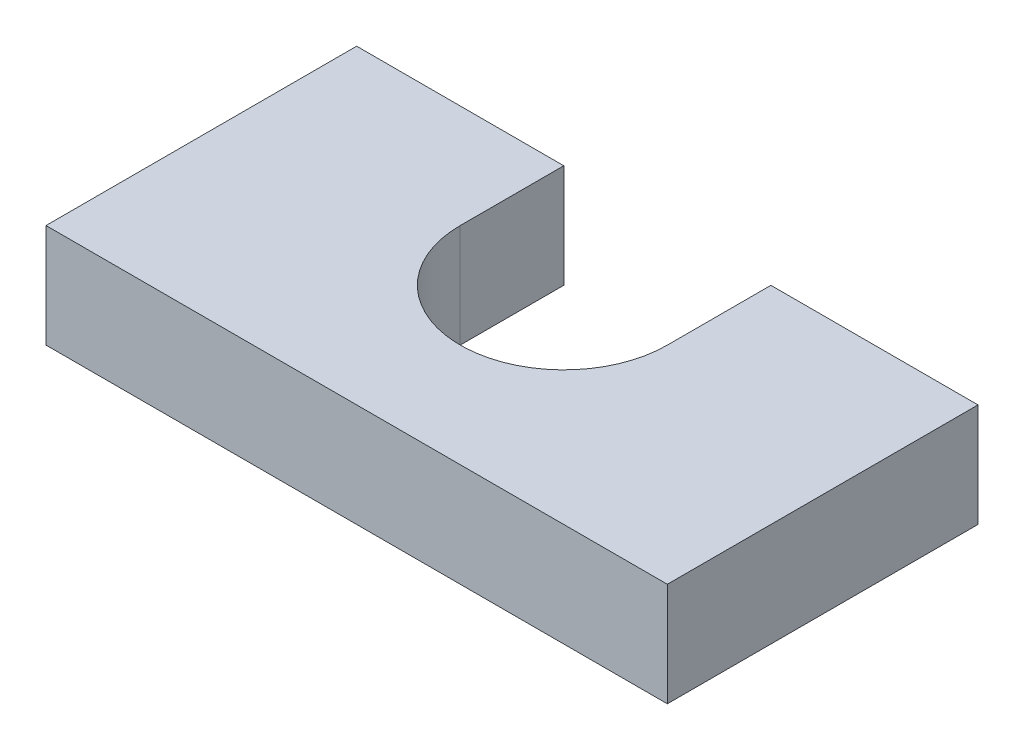
SolidWorks part; units mm, degrees
ref_plane "Přední rovina" through (0, 0, 0) normal (0, 0, 1) x (1, 0, 0)
ref_plane "Horní rovina" through (0, 0, 0) normal (0, 1, 0) x (1, 0, 0)
ref_plane "Pravá rovina" through (0, 0, 0) normal (1, 0, 0) x (0, 0, -1)
sketch "Sketch2" plane through (0, 0, 0) normal (0, 1, 0) x (1, 0, 0)
  line L0 (-20, 0) -> (-20, -20)
  line L3 (60, -60) -> (-60, -60)
  line L4 (-60, -60) -> (-60, 0)
  line L5 (-60, 0) -> (-20, 0)
  line L6 (0, 0) -> (0, -60) construction
  line L7 (60, 0) -> (20, 0)
  line L8 (60, -60) -> (60, 0)
  line L9 (20, 0) -> (20, -20)
  arc A0 (-20, -20) -> (20, -20) centre (0, -20) ccw
  point P4 (-30, -31.1559)
  dimension "D2" = 20
  dimension "D1" = 40
  dimension "D3" = 60
  dimension "D4" = 20
extrude "Boss-Extrude1" add sketch "Sketch2" along normal blind 20
equation "\"R\"= 20"
equation "\"D2@Sketch2\"=\"R\""
equation "\"D1@Sketch2\"=\"R\" *2"
equation "\"D3@Sketch2\"=\"R\"*3"
equation "\"D4@Sketch2\"=\"R\""
